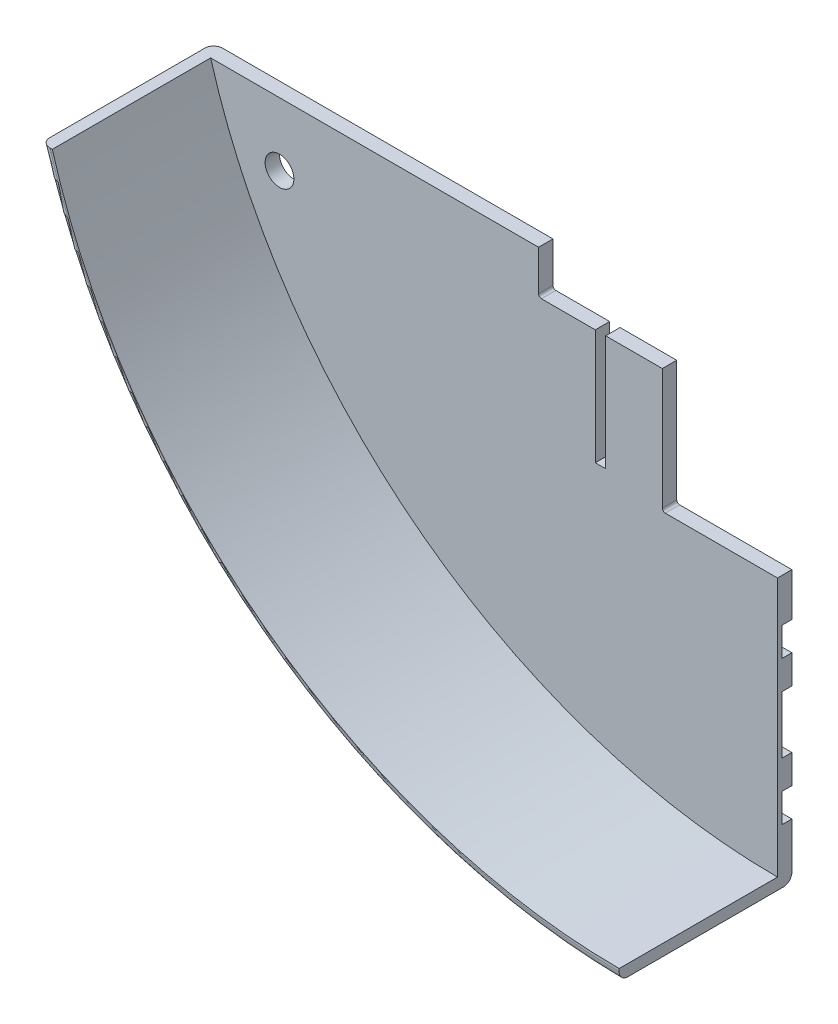
SolidWorks part; units mm, degrees
ref_plane "Alzado" through (0, 0, 0) normal (0, 0, 1) x (1, 0, 0)
ref_plane "Planta" through (0, 0, 0) normal (0, 1, 0) x (1, 0, 0)
ref_plane "Vista lateral" through (0, 0, 0) normal (1, 0, 0) x (0, 0, -1)
sketch "Sketch1" plane through (0, 0, 0) normal (0, 0, 1) x (1, 0, 0)
  line L0 (-4.5424, -76.7188) -> (-4.5424, -6.7188)
  line L2 (-87.5424, 56.2812) -> (-177.5424, 56.2812) construction
  line L3 (-44.5424, 13.2812) -> (-44.5424, 56.2812)
  line L4 (-44.5424, 56.2812) -> (-64.2424, 56.2812)
  line L5 (-87.5424, 56.2812) -> (-87.5424, 71.2812)
  line L8 (-4.5424, -76.7188) -> (-4.5424, -80.7188)
  line L10 (-4.5424, -6.7188) -> (-4.5424, 13.2812)
  line L11 (-4.5424, 13.2812) -> (-44.5424, 13.2812)
  line L12 (-177.5424, 56.2812) -> (-177.5424, 49.2812) construction
  line L13 (-67.8424, 56.2812) -> (-67.8424, 16.2812)
  line L14 (-64.2424, 56.2812) -> (-64.2424, 16.2812)
  line L15 (-67.8424, 16.2812) -> (-64.2424, 16.2812)
  line L16 (-67.8424, 56.2812) -> (-87.5424, 56.2812)
  line L17 (-87.5424, 71.2812) -> (-205.4056, 71.2812)
  arc A0 (-201.4586, 71.2812) -> (-4.5424, -76.7188) centre (-4.5424, 128.2812) ccw
  arc A1 (-205.4056, 71.2812) -> (-4.5424, -80.7188) centre (-2.2681, 131.0038) ccw
  circle A2 centre (-177.5424, 49.2812) radius 5
  dimension "D6" = 205
  dimension "D8" = 20
  dimension "D3" = 10
  dimension "D1" = 70
  dimension "D2" = 90
  dimension "D4" = 43
  dimension "D9" = 4
  dimension "D10" = 7
  dimension "D11" = 40
  dimension "D12" = 3.6
extrude "Boss-Extrude1" add sketch "Sketch1" along normal blind 60
sketch "Sketch2" plane through (0, 0, 60) normal (0, 0, 1) x (1, 0, 0)
  line L15 (-4.5424, 71.2812) -> (-4.5424, -76.7188)
  line L16 (-201.4586, 71.2812) -> (-4.5424, 71.2812)
  line L17 (-87.5424, 71.2812) -> (-205.4056, 71.2812) construction
  arc A0 (-201.4586, 71.2812) -> (-4.5424, -76.7188) centre (-4.5424, 128.2812) ccw
extrude "Cut-Extrude1" cut sketch "Sketch2" against normal blind 55
sketch "Sketch3" plane through (0, 0, 0) normal (0, 0, -1) x (-1, 0, 0)
  line L0 (4.5424, -76.7188) -> (4.5424, -6.7188) construction
  line L1 (4.5424, -61.7188) -> (49.5424, -61.7188)
  line L2 (4.5424, -61.7188) -> (4.5424, -51.7188)
  line L3 (4.5424, -1.7188) -> (49.5424, -1.7188)
  line L4 (49.5424, -61.7188) -> (49.5424, -51.7188)
  line L5 (4.5424, -11.7188) -> (4.5424, -1.7188)
  line L6 (4.5424, -51.7188) -> (39.5424, -51.7188)
  line L8 (4.5424, -11.7188) -> (39.5424, -11.7188)
  line L12 (49.5424, -21.7188) -> (49.5424, -1.7188)
  line L13 (39.5424, -11.7188) -> (39.5424, -51.7188)
  line L14 (49.5424, -21.7188) -> (49.5424, -51.7188)
  dimension "D1" = 10
  dimension "D2" = 10
  dimension "D3" = 10
  dimension "D4" = 45
  dimension "D5" = 15
  dimension "D6" = 60
extrude "Cut-Extrude2" cut sketch "Sketch3" against normal blind 3.5
fillet "Fillet1" radius 3 2 edges at (-130.0355, -37.8368, 60) (-130.0355, -37.8368, 0)
sketch "Sketch4" plane through (0, 0, 0) normal (0, 0, -1) x (-1, 0, 0)
  line L0 (102.8424, -4.0393) -> (133.341, -4.0393) construction
  line L1 (87.5424, 71.2812) -> (202.2767, 71.2812) construction
  line L6 (102.8424, -4.0393) -> (134.0193, 13.9607)
  line L7 (134.0193, 13.9607) -> (124.0193, 31.2812)
  line L8 (67.8424, 56.2812) -> (67.8424, 16.2812) construction
  line L9 (4.5424, -21.7188) -> (22.5424, -21.7188)
  line L10 (124.0193, 31.2812) -> (92.8424, 13.2812)
  line L11 (92.8424, 13.2812) -> (102.8424, -4.0393)
  line L12 (4.5424, -51.7188) -> (4.5424, -11.7188) construction
  line L13 (22.5424, -21.7188) -> (22.5424, -41.7188)
  line L14 (22.5424, -41.7188) -> (4.5424, -41.7188)
  line L15 (4.5424, -41.7188) -> (4.5424, -21.7188)
  line L17 (4.5424, -11.7188) -> (39.5424, -11.7188) construction
  dimension "D1" = 36
  dimension "D2" = 90
  dimension "D3" = 20
  dimension "D4" = 30
  dimension "D5" = 25
  dimension "D6" = 40
  dimension "D7" = 18
  dimension "D8" = 20
  dimension "D9" = 10
extrude "Cut-Extrude3" cut sketch "Sketch4" against normal blind 3.5
sketch "Sketch5" plane through (0, 0, 0) normal (0, 0, 1) x (1, 0, 0)
  line L0 (-124.0193, 31.2812) -> (-102.8424, -4.0393) construction
  line L1 (-92.8424, 13.2812) -> (-134.0193, 13.9607) construction
  line L2 (-4.5424, -46.7188) -> (-113.4308, -46.7188) construction
  line L3 (-4.5424, -51.7188) -> (-4.5424, -41.7188) construction
  line L4 (-113.4308, 13.6209) -> (-113.4308, -46.7188) construction
  dimension "D1" = 108.8885
  dimension "D2" = 60.3397
fillet "Fillet3" radius 7 6 edges at (-124.0193, 31.2812, 1.75) (-92.8424, 13.2812, 1.75) (-102.8424, -4.0393, 1.75) (-134.0193, 13.9607, 1.75) (-22.5424, -41.7188, 1.75) (-22.5424, -21.7188, 1.75)
fillet "Fillet4" radius 1 2 edges at (-44.5424, 13.2812, 2.5) (-87.5424, 56.2812, 2.5)
fillet "Fillet5" radius 8 2 edges at (-49.5424, -1.7188, 1.75) (-49.5424, -61.7188, 1.75)
fillet "Fillet6" radius 5 2 edges at (-39.5424, -51.7188, 1.75) (-39.5424, -11.7188, 1.75)
